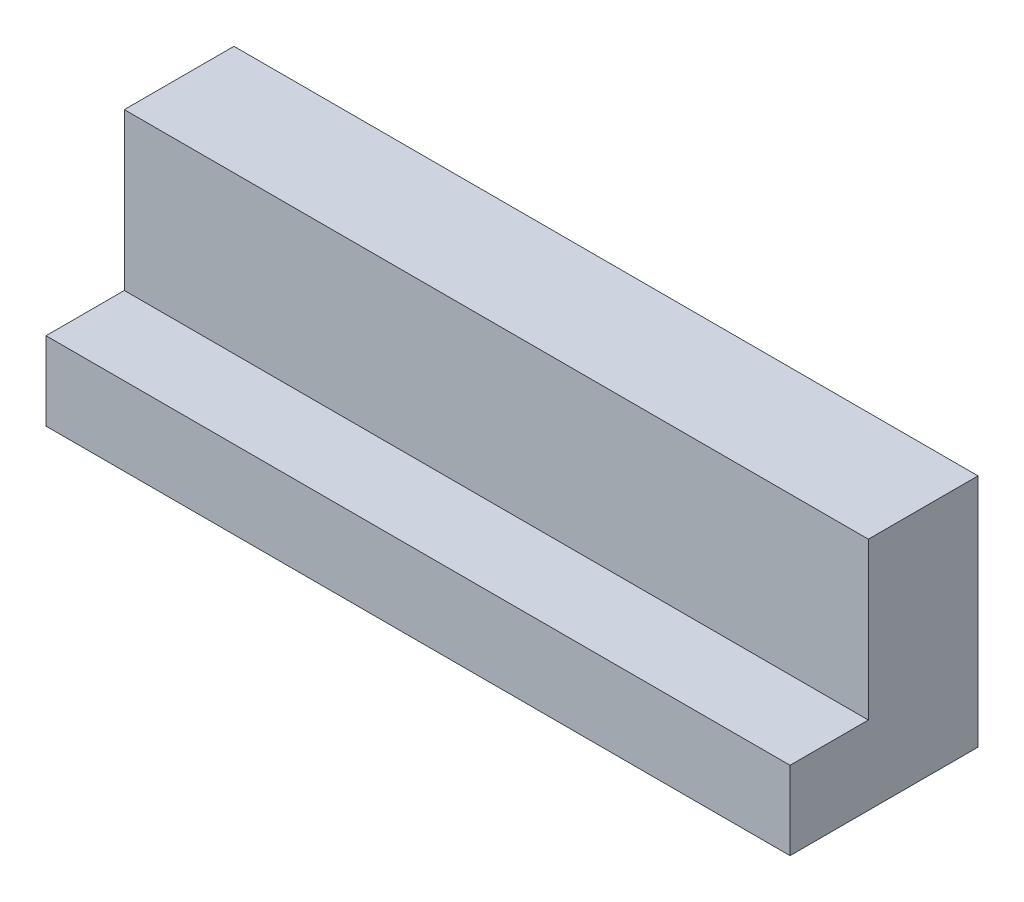
SolidWorks part; units mm, degrees
ref_plane "Front Plane" through (0, 0, 0) normal (0, 0, 1) x (1, 0, 0)
ref_plane "Top Plane" through (0, 0, 0) normal (0, 1, 0) x (1, 0, 0)
ref_plane "Right Plane" through (0, 0, 0) normal (1, 0, 0) x (0, 0, -1)
sketch "Sketch1" plane through (0, 0, 0) normal (0, 0, 1) x (1, 0, 0)
  line L0 (5.7994, -3.5) -> (57.7824, -3.5) construction
  line L1 (39.7824, -1.7) -> (20.7824, -1.7)
  line L2 (39.7824, -1.7) -> (39.7824, 4.3)
  line L3 (39.7824, 4.3) -> (20.7824, 4.3)
  line L4 (20.7824, -1.7) -> (20.7824, 4.3)
  line L5 (57.7824, -3.5) -> (57.7824, 130.2602) construction
  dimension "D1" = 1.8
  dimension "D2" = 6
  dimension "D3" = 18
  dimension "D4" = 19
extrude "Boss-Extrude1" add sketch "Sketch1" along normal blind 2.8
sketch "Sketch2" plane through (0, 0, 2.8) normal (0, 0, 1) x (1, 0, 0)
  line L0 (20.7824, 4.3) -> (20.7824, -1.7) construction
  line L1 (39.7824, -1.7) -> (20.7824, -1.7)
  line L2 (39.7824, -1.7) -> (39.7824, 0.3)
  line L3 (39.7824, 0.3) -> (20.7824, 0.3)
  line L4 (20.7824, -1.7) -> (20.7824, 0.3)
  line L5 (5.7994, -3.5) -> (57.7824, -3.5) construction
  dimension "D1" = 3.8
extrude "Boss-Extrude2" add sketch "Sketch2" along normal blind 2
